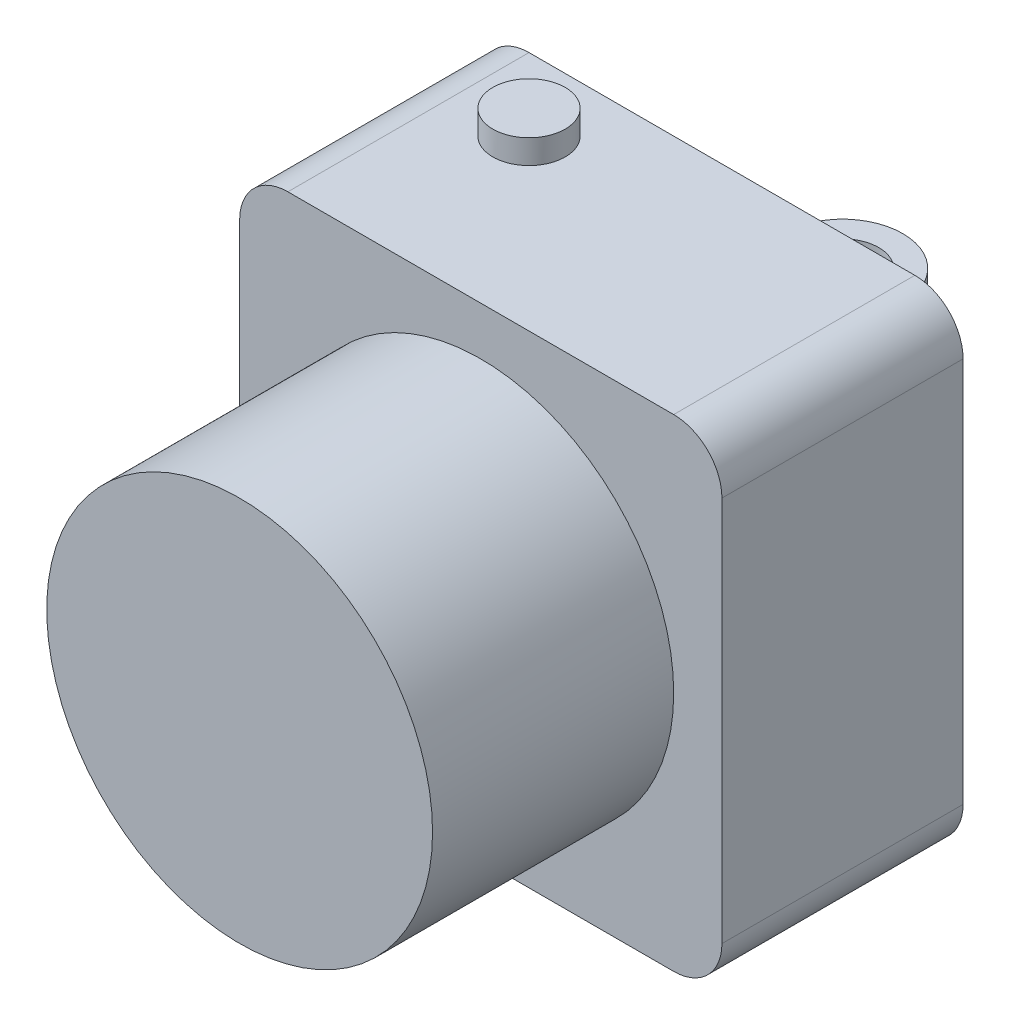
SolidWorks part; units mm, degrees
material "C-Glass Fiber"
ref_plane "Front Plane" through (0, 0, 0) normal (0, 0, 1) x (1, 0, 0)
ref_plane "Top Plane" through (0, 0, 0) normal (0, 1, 0) x (1, 0, 0)
ref_plane "Right Plane" through (0, 0, 0) normal (1, 0, 0) x (0, 0, -1)
sketch "Sketch1" plane through (0, 0, 0) normal (0, 0, 1) x (1, 0, 0)
  line L1 (-12.7, 12.7) -> (12.7, 12.7)
  line L2 (-12.7, 12.7) -> (-12.7, -12.7)
  line L3 (-12.7, -12.7) -> (12.7, -12.7)
  line L4 (12.7, 12.7) -> (12.7, -12.7)
  line L5 (-12.7, 12.7) -> (12.7, -12.7) construction
  line L6 (-12.7, -12.7) -> (12.7, 12.7) construction
  dimension "D2" = 25.4
extrude "Boss-Extrude1" add sketch "Sketch1" along normal mid plane 25.4
sketch "Sketch3" plane through (0, 0, 12.7) normal (0, 0, 1) x (1, 0, 0)
  line L0 (12.7, 12.7) -> (-12.7, 12.7) construction
  line L1 (-12.7, -12.7) -> (12.7, -12.7)
  line L2 (-12.7, -12.7) -> (-12.7, 12.7)
  line L3 (-12.7, 12.7) -> (12.7, 12.7)
  line L4 (12.7, -12.7) -> (12.7, 12.7)
  line L5 (-12.7, -12.7) -> (12.7, 12.7) construction
  line L6 (-12.7, 12.7) -> (12.7, -12.7) construction
  line L7 (12.7, -12.7) -> (12.7, 12.7) construction
  circle A0 centre (0, 0) radius 10.16
  dimension "D1" = 20.32
extrude "Cut-Extrude1" cut sketch "Sketch3" against normal blind 12.7
fillet "Fillet1" radius 2.54 4 edges at (-12.7, -12.7, -6.35) (-12.7, 12.7, -6.35) (12.7, 12.7, -6.35) (12.7, -12.7, -6.35)
sketch "Sketch4" plane through (0, 12.7, 0) normal (0, 1, 0) x (1, 0, 0)
  line L0 (10.16, 12.7) -> (-10.16, 12.7) construction
  line L1 (-12.7, 0) -> (-12.7, 12.7) construction
  circle A0 centre (-6.35, 8.89) radius 1.905
  dimension "D1" = 3.81
  dimension "D2" = 3.81
  dimension "D3" = 6.35
extrude "Boss-Extrude3" add sketch "Sketch4" along normal mid plane 2.54
ref_plane "Plane1" through (0, 4.7625, 0) normal (0, 1, 0) x (1, 0, 0)
sketch "Sketch5" plane through (0, 4.7625, 0) normal (0, 1, 0) x (1, 0, 0)
  line L0 (10.16, 12.7) -> (-10.16, 12.7) construction
  line L1 (-3.175, 12.7) -> (3.175, 12.7)
  line L2 (-3.175, 12.7) -> (-3.175, 19.05)
  line L4 (3.175, 12.7) -> (3.175, 19.05)
  line L5 (0, 0) -> (0, 23.0664) construction
  arc A0 (3.175, 19.05) -> (-3.175, 19.05) centre (0, 19.05) ccw
  circle A1 centre (0, 19.05) radius 1.905
  dimension "D2" = 3.81
  dimension "D1" = 6.35
  dimension "D3" = 6.35
extrude "Boss-Extrude4" add sketch "Sketch5" against normal blind 9.525
